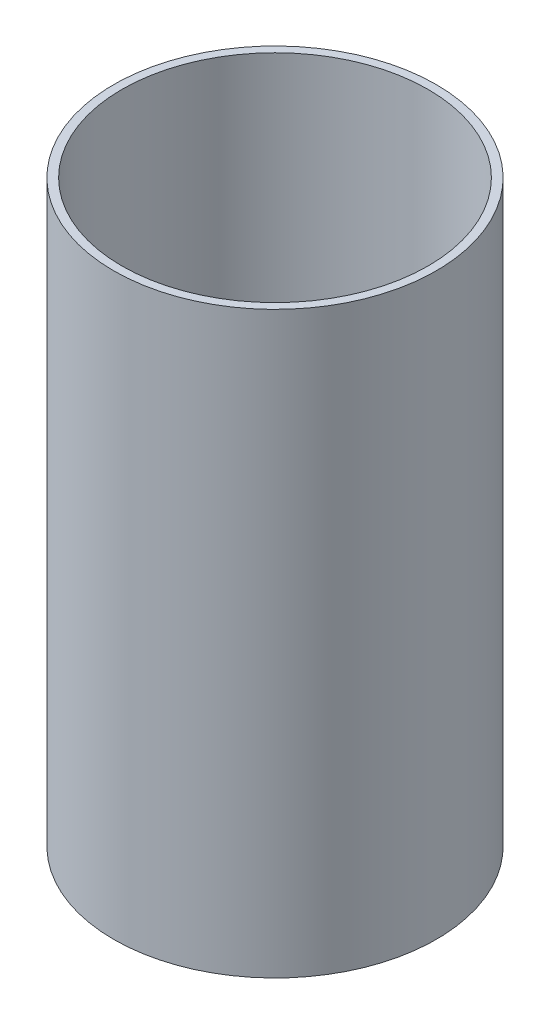
SolidWorks part; units mm, degrees
other "Markup1"
sketch "Sketch3" plane through (-49.53, 177.8, -49.53) normal (-0.149, 0.762, -0.6302) x (-0.1195, 0.6187, 0.7765)
ref_plane "Front Plane" through (0, 0, 0) normal (0, 0, 1) x (1, 0, 0)
ref_plane "Top Plane" through (0, 0, 0) normal (0, 1, 0) x (1, 0, 0)
ref_plane "Right Plane" through (0, 0, 0) normal (1, 0, 0) x (0, 0, -1)
sketch "Sketch2" plane through (0, 0, 0) normal (0, 1, 0) x (1, 0, 0)
  circle A0 centre (0, 0) radius 49.53
  circle A1 centre (0, 0) radius 46.99
  dimension "D1" = 99.06
  dimension "D2" = 2.54
extrude "Boss-Extrude1" add sketch "Sketch2" along normal blind 177.8
